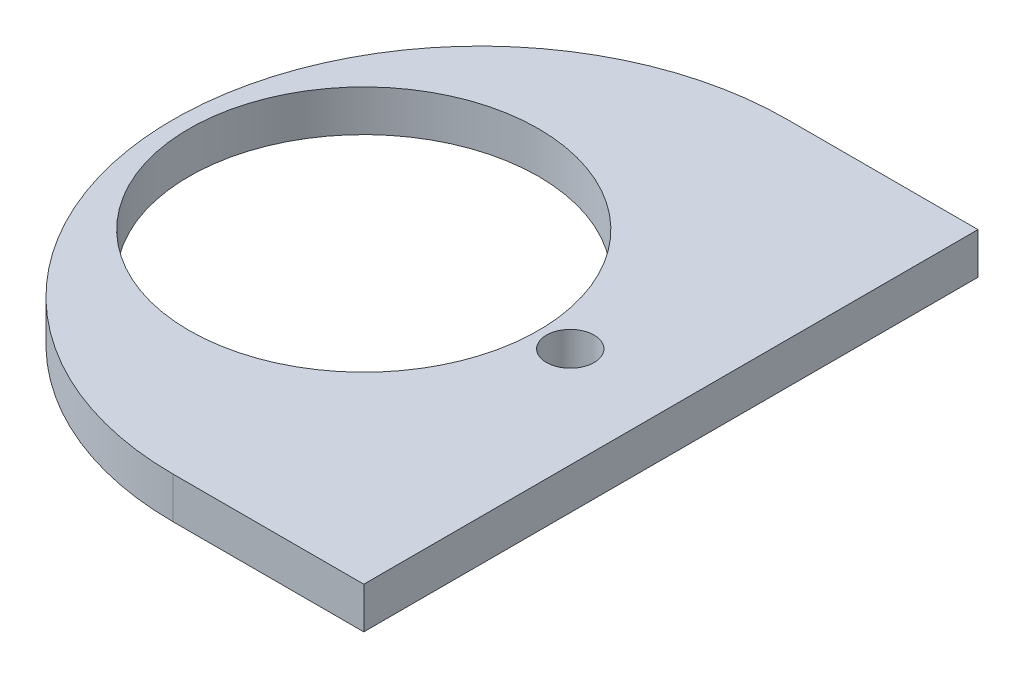
SolidWorks part; units mm, degrees
ref_plane "Front Plane" through (0, 0, 0) normal (0, 0, 1) x (1, 0, 0)
ref_plane "Top Plane" through (0, 0, 0) normal (0, 1, 0) x (1, 0, 0)
ref_plane "Right Plane" through (0, 0, 0) normal (1, 0, 0) x (0, 0, -1)
sketch "Sketch1" plane through (0, 0, 0) normal (0, 1, 0) x (1, 0, 0)
  line L0 (0, 0) -> (36, 0)
  line L1 (36, 0) -> (36, -116)
  line L2 (36, -116) -> (0, -116)
  circle A1 centre (-22, -58) radius 33
  arc A3 (0, 0) -> (0, -116) centre (0, -58) ccw
  circle A4 centre (17, -58) radius 4.5
  dimension "D1" = 58
  dimension "D4" = 66
  dimension "D5" = 9
  dimension "D2" = 116
  dimension "D3" = 36
  dimension "D6" = 39
extrude "Boss-Extrude1" add sketch "Sketch1" along normal blind 7.8
